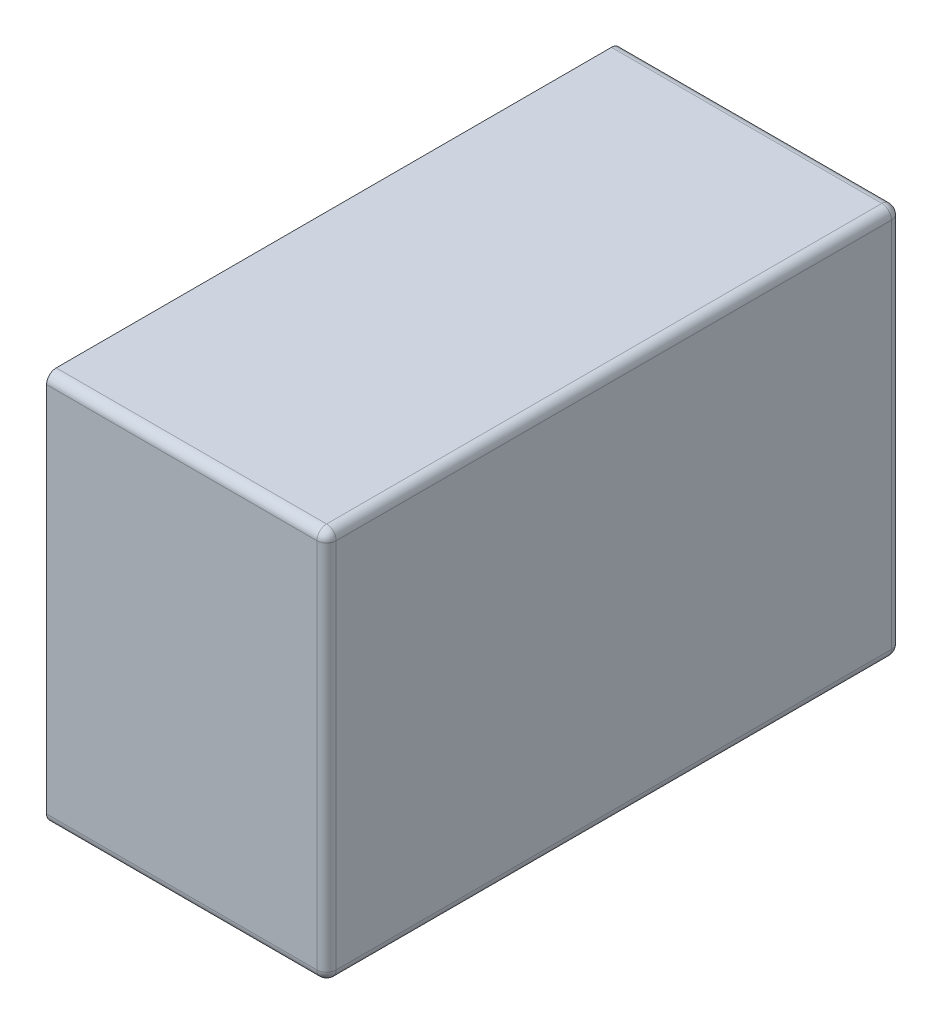
SolidWorks part; units mm, degrees
ref_plane "Front Plane" through (0, 0, 0) normal (0, 0, 1) x (1, 0, 0)
ref_plane "Top Plane" through (0, 0, 0) normal (0, 1, 0) x (1, 0, 0)
ref_plane "Right Plane" through (0, 0, 0) normal (1, 0, 0) x (0, 0, -1)
sketch "Sketch1" plane through (0, 0, 0) normal (0, 1, 0) x (1, 0, 0)
  line L1 (-145, 297.5) -> (145, 297.5)
  line L2 (-145, 297.5) -> (-145, -297.5)
  line L3 (-145, -297.5) -> (145, -297.5)
  line L4 (145, 297.5) -> (145, -297.5)
  line L5 (-145, 297.5) -> (145, -297.5) construction
  line L6 (-145, -297.5) -> (145, 297.5) construction
  point P0 (0, 0)
  dimension "D1" = 290
  dimension "D2" = 595
extrude "Boss-Extrude2" add sketch "Sketch1" along normal blind 405
fillet "Fillet3" radius 10 8 edges at (145, 0, 0) (145, 202.5, -297.5) (145, 405, 0) (145, 202.5, 297.5) (0, 405, 297.5) (0, 0, 297.5) (0, 0, -297.5) (0, 405, -297.5)
sketch "Sketch3" plane through (-145, 0, 0) normal (-1, 0, 0) x (0, 0, 1)
  line L0 (0, 405) -> (0, 0) construction
  line L1 (-287.5, 405) -> (287.5, 405) construction
  line L2 (-297.5, 395) -> (-297.5, 10) construction
  line L3 (-287.5, 395) -> (287.5, 395)
  line L4 (-287.5, 395) -> (-287.5, 10)
  line L5 (-287.5, 10) -> (287.5, 10)
  line L6 (287.5, 395) -> (287.5, 10)
  line L7 (-287.5, 395) -> (287.5, 10) construction
  line L8 (-287.5, 10) -> (287.5, 395) construction
  point P5 (0, 202.5)
  dimension "D1" = 10
  dimension "D2" = 10
extrude "Cut-Extrude2" cut sketch "Sketch3" against normal blind 270
